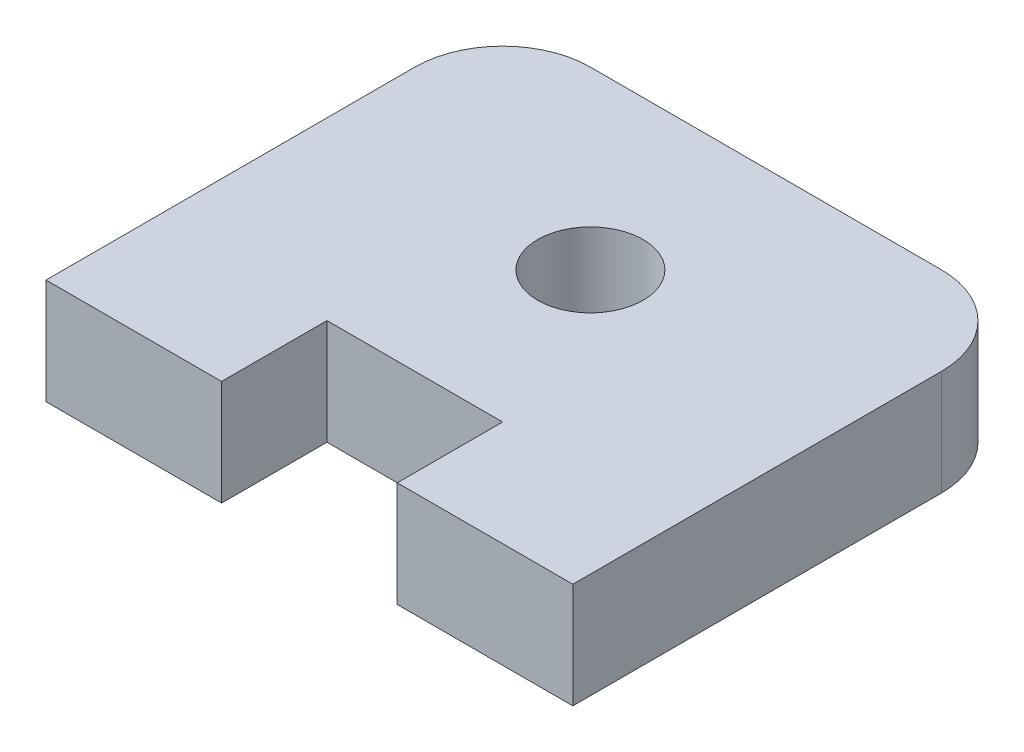
SolidWorks part; units mm, degrees
ref_plane "Front Plane" through (0, 0, 0) normal (0, 0, 1) x (1, 0, 0)
ref_plane "Top Plane" through (0, 0, 0) normal (0, 1, 0) x (1, 0, 0)
ref_plane "Right Plane" through (0, 0, 0) normal (1, 0, 0) x (0, 0, -1)
sketch "Sketch1" plane through (0, 0, 0) normal (0, 1, 0) x (1, 0, 0)
  line L0 (0, 0) -> (0, 10.5)
  line L1 (2.5, 13) -> (12.5, 13)
  line L2 (15, 10.5) -> (15, 0)
  line L3 (15, 0) -> (10, 0)
  line L4 (10, 0) -> (10, 3)
  line L5 (10, 3) -> (5, 3)
  line L6 (5, 3) -> (5, 0)
  line L7 (5, 0) -> (0, 0)
  circle A0 centre (7.5, 8) radius 1.5
  arc A1 (12.5, 13) -> (15, 10.5) centre (12.5, 10.5) cw
  arc A2 (0, 10.5) -> (2.5, 13) centre (2.5, 10.5) cw
  dimension "D5" = 5
  dimension "D6" = 7.5
  dimension "D7" = 3
  dimension "D8" = 2.5
  dimension "D1" = 5
  dimension "D2" = 3
  dimension "D3" = 5
  dimension "D4" = 10
extrude "Boss-Extrude1" add sketch "Sketch1" along normal blind 3
